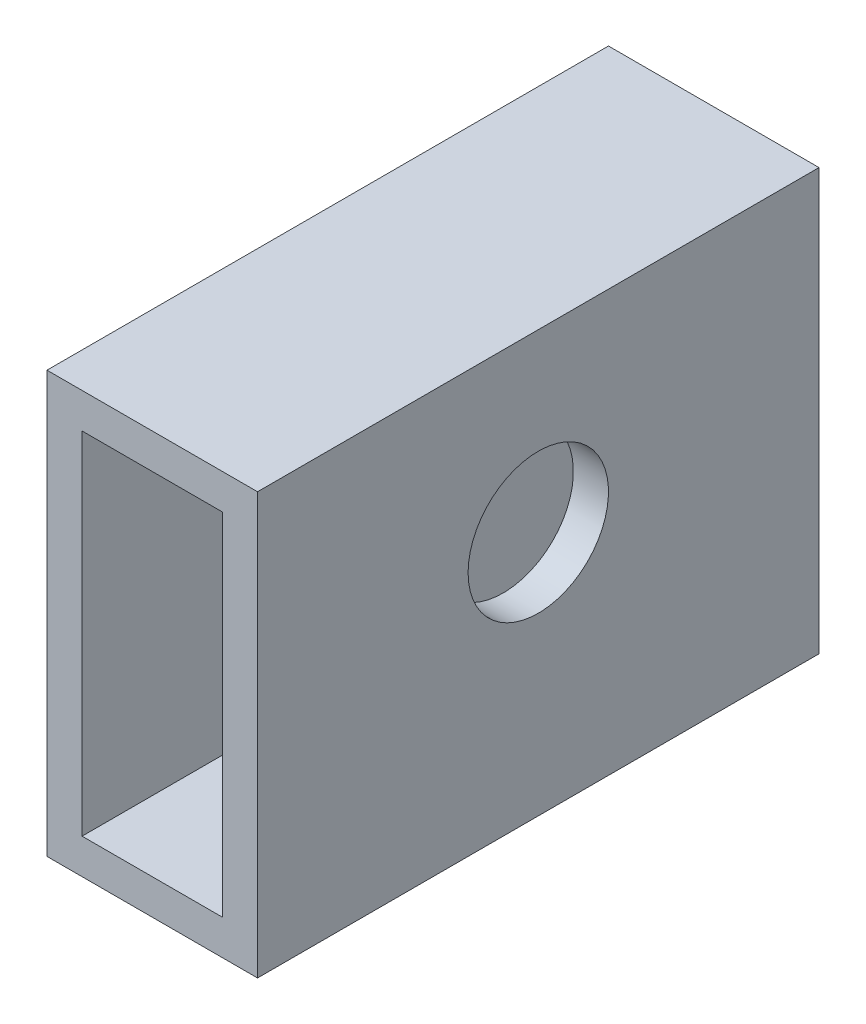
SolidWorks part; units mm, degrees
ref_plane "Front Plane" through (0, 0, 0) normal (0, 0, 1) x (1, 0, 0)
ref_plane "Top Plane" through (0, 0, 0) normal (0, 1, 0) x (1, 0, 0)
ref_plane "Right Plane" through (0, 0, 0) normal (1, 0, 0) x (0, 0, -1)
sketch "Sketch1" plane through (0, 0, 0) normal (0, 0, 1) x (1, 0, 0)
  line L1 (0, 0) -> (19.05, 0)
  line L2 (0, 0) -> (0, 38.1)
  line L3 (0, 38.1) -> (19.05, 38.1)
  line L4 (19.05, 0) -> (19.05, 38.1)
  dimension "D1" = 38.1
  dimension "D2" = 19.05
extrude "Extrude-Thin1" add sketch "Sketch1" along normal blind 50.8 thin thin type one direction reverse wall 3.175
sketch "Sketch3" plane through (0, 0, 0) normal (-1, 0, 0) x (0, 0, 1)
  line L0 (50.8, 0) -> (0, 0) construction
  circle A0 centre (25.4, 22.225) radius 6.35
  point P3 (0, 19.05)
  point P8 (25.4, 0)
  dimension "D1" = 12.7
  dimension "D2" = 22.225
extrude "Cut-Extrude2" cut sketch "Sketch3" against normal through all
